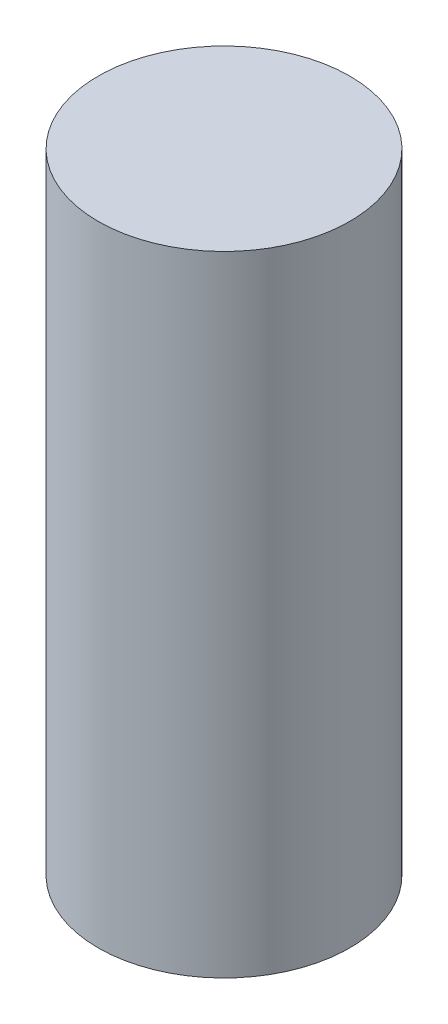
SolidWorks part; units mm, degrees
ref_plane "Front Plane" through (0, 0, 0) normal (0, 0, 1) x (1, 0, 0)
ref_plane "Top Plane" through (0, 0, 0) normal (0, 1, 0) x (1, 0, 0)
ref_plane "Right Plane" through (0, 0, 0) normal (1, 0, 0) x (0, 0, -1)
sketch "Sketch1" plane through (0, 0, 0) normal (0, 1, 0) x (1, 0, 0)
  circle A0 centre (0, 0) radius 20
  dimension "D1" = 40
extrude "Boss-Extrude1" add sketch "Sketch1" along normal blind 100
sketch "Sketch2" plane through (0, 0, 0) normal (0, -1, 0) x (1, 0, 0)
  circle A0 centre (0, 0) radius 10
  circle A1 centre (0, 22) radius 5
  circle A2 centre (0, -22) radius 5
  dimension "D2" = 10
  dimension "D3" = 20
  dimension "D4" = 10
  dimension "D1" = 22
  dimension "D5" = 22
extrude "Cut-Extrude1" cut sketch "Sketch2" against normal blind 20 contours A0
